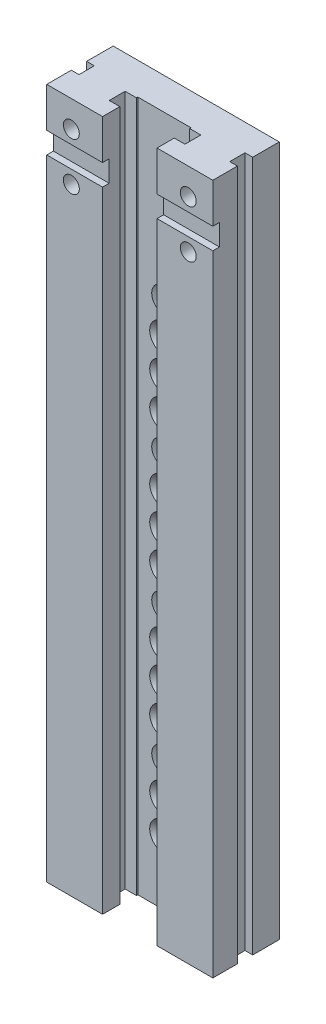
SolidWorks part; units mm, degrees
ref_plane "Front Plane" through (0, 0, 0) normal (0, 0, 1) x (1, 0, 0)
ref_plane "Top Plane" through (0, 0, 0) normal (0, 1, 0) x (1, 0, 0)
ref_plane "Right Plane" through (0, 0, 0) normal (1, 0, 0) x (0, 0, -1)
sketch "Sketch1" plane through (0, 0, 0) normal (0, 1, 0) x (1, 0, 0)
  line L0 (62.5, 0) -> (-62.5, 0)
  line L1 (-62.5, 0) -> (-62.5, -20)
  line L2 (-62.5, -20) -> (-56.7, -20)
  line L3 (-56.7, -20) -> (-56.7, -31.5)
  line L4 (-56.7, -31.5) -> (-62.5, -31.5)
  line L5 (-62.5, -31.5) -> (-62.5, -50)
  line L6 (-62.5, -50) -> (-20.5, -50)
  line L7 (62.5, -50) -> (62.5, -31.5)
  line L8 (62.5, -31.5) -> (56.7, -31.5)
  line L9 (56.7, -31.5) -> (56.7, -20)
  line L10 (56.7, -20) -> (62.5, -20)
  line L11 (62.5, -20) -> (62.5, 0)
  line L12 (-20.5, -50) -> (-20.5, -37)
  line L13 (-20.5, -37) -> (-28.5, -37)
  line L14 (-28.5, -37) -> (-28.5, -25)
  line L16 (28.5, -25) -> (28.5, -37)
  line L17 (28.5, -37) -> (20.5, -37)
  line L18 (20.5, -37) -> (20.5, -50)
  line L19 (20.5, -50) -> (62.5, -50)
  line L20 (0, 37.3611) -> (0, -33.9776) construction
  line L24 (-28.5, -25) -> (28.5, -25)
  dimension "G" = 11.5
  dimension "A" = 50
  dimension "J" = 20
  dimension "B" = 125
  dimension "H" = 13
  dimension "E" = 41
  dimension "D" = 57
  dimension "D9" = 5.8
  dimension "AA" = 12
extrude "Boss-Extrude1" add sketch "Sketch1" against normal blind 520
sketch "Sketch4" plane through (0, 0, 0) normal (0, 1, 0) x (1, 0, 0)
  line L0 (-28.5, -25) -> (28.5, -25) construction
  line L1 (-20, -25) -> (20, -25)
  line L2 (-20, -25) -> (-20, -24)
  line L3 (-20, -24) -> (20, -24)
  line L4 (20, -25) -> (20, -24)
  line L5 (0, 0) -> (25.1088, 0) construction
  line L6 (0, -25) -> (0, 0) construction
  dimension "D1" = 40
  dimension "D2" = 1
extrude "Cut-Extrude1" cut sketch "Sketch4" against normal up to next
hole_wizard "CBORE for M12 Hex Head Bolt1" positions "Sketch3" profile "Sketch2" counterbore size "M12" standard "ISO" end condition through all
sketch "Sketch3" plane through (0, 0, 25) normal (0, 0, 1) x (1, 0, 0)
  line L0 (20, 0) -> (-20, 0) construction
  line L1 (0, 0) -> (0, -122.5) construction
  point P0 (0, -122.5)
  dimension "D1" = 122.5
sketch "Sketch2" plane through (0, -122.5, 25) normal (1, 0, 0) x (0, -1, 0)
  line L0 (0, 0) -> (0, 25)
  line L1 (0, 25) -> (6.5, 25)
  line L3 (6.5, 25) -> (6.5, 12)
  line L4 (6.5, 12) -> (9.5, 12)
  line L5 (9.5, 12) -> (9.5, 0)
  line L7 (9.5, 0) -> (0, 0)
  line L11 (0, -6.35) -> (0, 107.95) construction
  dimension "Thru Hole Dia." = 13
  dimension "Thru Hole Depth" = 25
  dimension "C'Bore Dia." = 19
  dimension "C'Bore Depth" = 12
pattern_linear "LPattern1" count 4 spacing 100 along (0, -1, 0) of "CBORE for M12 Hex Head Bolt1"
hole_wizard "CSK for M10 Countersunk Flat Head Screw1" positions "Sketch5" profile "Sketch6" countersink size "M10" standard "ISO"
sketch "Sketch5" plane through (0, 0, 24) normal (0, 0, 1) x (1, 0, 0)
  line L0 (20, 0) -> (-20, 0) construction
  line L1 (0, 0) -> (0, -147.5) construction
  point P0 (0, -147.5)
  dimension "D1" = 147.5
sketch "Sketch6" plane through (0, -147.5, 24) normal (1, 0, 0) x (0, -1, 0)
  line L0 (0, 0) -> (0, 14.3047)
  line L1 (0, 14.3047) -> (5.5, 11)
  line L2 (5.5, 11) -> (5.5, 5.5)
  line L3 (5.5, 5.5) -> (11, 0)
  line L5 (11, 0) -> (0, 0)
  line L6 (-5.5, 5.5) -> (-11, 0) construction
  line L10 (0, 14.3047) -> (-5.5, 11) construction
  line L11 (0, -6.35) -> (0, 107.95) construction
  dimension "Hole Dia." = 11
  dimension "Hole Depth" = 11
  dimension "Near C'Sink Dia." = 22
  dimension "Near C'Sink Angle" = 90
  dimension "Drill Angle" = 118
pattern_linear "LPattern2" count 14 spacing 25 along (0, -1, 0) skipping (3, 0), (7, 0), (11, 0) of "CSK for M10 Countersunk Flat Head Screw1"
sketch "Sketch7" plane through (62.5, 0, 0) normal (1, 0, 0) x (0, 0, -1)
  line L0 (-50, -520) -> (-50, 0) construction
  line L1 (-50, -46) -> (-45, -46)
  line L2 (-50, -46) -> (-50, -30)
  line L3 (-50, -30) -> (-45, -30)
  line L4 (-45, -46) -> (-45, -30)
  line L5 (-45, -38) -> (-50, -38) construction
  line L6 (-50, 0) -> (-31.5, 0) construction
  dimension "D1" = 30
  dimension "D2" = 16
  dimension "D3" = 5
extrude "Cut-Extrude2" cut sketch "Sketch7" against normal through all
hole_wizard "M14 Tapped Hole1" positions "Sketch8" profile "Sketch9" tap size "M14" standard "ISO"
sketch "Sketch8" plane through (0, 0, 50) normal (0, 0, 1) x (1, 0, 0)
  line L0 (62.5, -46) -> (62.5, -30) construction
  line L1 (62.5, -46) -> (62.5, -30) construction
  line L2 (62.5, -38) -> (7.6849, -38) construction
  line L4 (0, 0) -> (0, -63.7517) construction
  point P0 (44, -20)
  dimension "D1" = 18
  dimension "D2" = 44
sketch "Sketch9" plane through (44, -20, 50) normal (1, 0, 0) x (0, -1, 0)
  line L0 (0, 0) -> (0, 39.6052)
  line L1 (0, 39.6052) -> (6, 36)
  line L2 (6, 36) -> (6, 0)
  line L5 (6, 0) -> (0, 0)
  line L10 (0, 39.6052) -> (-6, 36) construction
  line L11 (0, -6.35) -> (0, 107.95) construction
  dimension "Tap Drill Dia." = 12
  dimension "Tap Drill Depth" = 36
  dimension "Drill Angle" = 118
cosmetic thread "Hole Thread1" parameters "D1"=28, "D2"=14
pattern_linear "LPattern3" count 2 spacing 88 along (-1, 0, 0) count 2 spacing 36 along (0, -1, 0) of "M14 Tapped Hole1"
